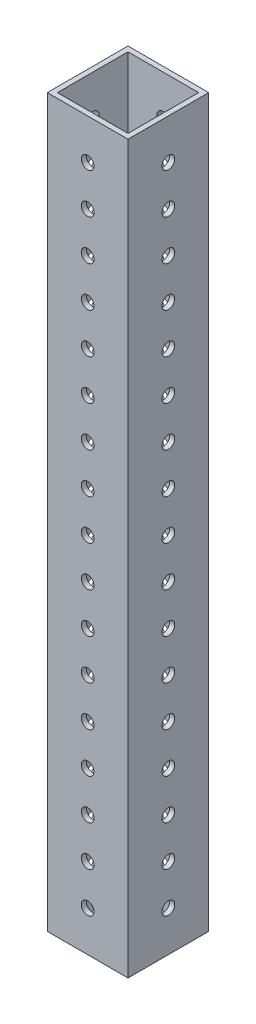
SolidWorks part; units mm, degrees
material "6061-T6 (SS)"
ref_plane "Front Plane" through (0, 0, 0) normal (0, 0, 1) x (1, 0, 0)
ref_plane "Top Plane" through (0, 0, 0) normal (0, 1, 0) x (1, 0, 0)
ref_plane "Right Plane" through (0, 0, 0) normal (1, 0, 0) x (0, 0, -1)
sketch "Sketch1" plane through (0, 0, 0) normal (0, 1, 0) x (1, 0, 0)
  line L0 (-11.1125, -11.1125) -> (-11.1125, 11.1125)
  line L1 (-12.7, -12.7) -> (12.7, -12.7)
  line L2 (-12.7, -12.7) -> (-12.7, 12.7)
  line L3 (-12.7, 12.7) -> (12.7, 12.7)
  line L4 (12.7, -12.7) -> (12.7, 12.7)
  line L5 (-12.7, -12.7) -> (12.7, 12.7) construction
  line L6 (-12.7, 12.7) -> (12.7, -12.7) construction
  line L7 (-11.1125, 11.1125) -> (11.1125, 11.1125)
  line L8 (11.1125, -11.1125) -> (11.1125, 11.1125)
  line L9 (-11.1125, -11.1125) -> (11.1125, -11.1125)
  point P0 (0, 0)
  dimension "D1" = 25.4
  dimension "D2" = 25.4
  dimension "D3" = 1.5875
extrude "Boss-Extrude1" add sketch "Sketch1" along normal blind 228.6
hole_wizard "#22 (0.157) Diameter Hole1" positions "Sketch2" profile "Sketch3" hole size "#22" standard "ANSI Inch" end condition through all
sketch "Sketch2" plane through (0, 0, 12.7) normal (0, 0, 1) x (1, 0, 0)
  line L0 (12.7, 228.6) -> (12.7, 0) construction
  line L1 (-12.7, 0) -> (12.7, 0) construction
  point P0 (0, 12.7)
  dimension "D1" = 12.7
  dimension "D2" = 12.7
sketch "Sketch3" plane through (0, 12.7, 12.7) normal (1, 0, 0) x (0, -1, 0)
  line L0 (0, 0) -> (0, 25.4)
  line L1 (0, 25.4) -> (1.9939, 25.4)
  line L2 (1.9939, 25.4) -> (1.9939, 0)
  line L5 (1.9939, 0) -> (0, 0)
  line L11 (0, -6.35) -> (0, 107.95) construction
  dimension "Thru Hole Dia." = 3.9878
  dimension "Thru Hole Depth" = 25.4
pattern_linear "LPattern1" count 17 spacing 12.7 along (0, 1, 0) of "#22 (0.157) Diameter Hole1"
hole_wizard "#22 (0.157) Diameter Hole2" positions "Sketch4" profile "Sketch5" hole size "#22" standard "ANSI Inch" end condition through all
sketch "Sketch4" plane through (12.7, 0, 0) normal (1, 0, 0) x (0, 0, -1)
  line L2 (-12.7, 228.6) -> (-12.7, 0) construction
  line L3 (-12.7, 0) -> (12.7, 0) construction
  point P0 (0, 12.7)
  dimension "D1" = 12.7
  dimension "D2" = 12.7
sketch "Sketch5" plane through (12.7, 12.7, 0) normal (0, 1, 0) x (0, 0, -1)
  line L0 (0, 0) -> (0, 25.4)
  line L1 (0, 25.4) -> (1.9939, 25.4)
  line L2 (1.9939, 25.4) -> (1.9939, 0)
  line L5 (1.9939, 0) -> (0, 0)
  line L11 (0, -6.35) -> (0, 107.95) construction
  dimension "Thru Hole Dia." = 3.9878
  dimension "Thru Hole Depth" = 25.4
pattern_linear "LPattern2" count 17 spacing 12.7 along (0, 1, 0) of "#22 (0.157) Diameter Hole2"
